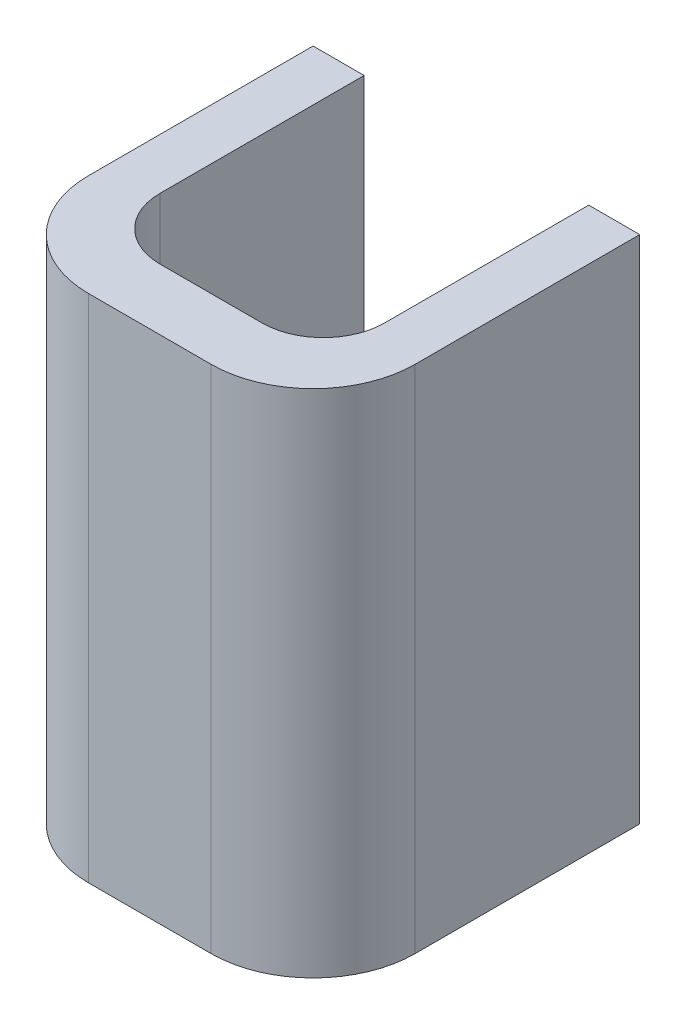
SolidWorks part; units mm, degrees
ref_plane "前视基准面" through (0, 0, 0) normal (0, 0, 1) x (1, 0, 0)
ref_plane "上视基准面" through (0, 0, 0) normal (0, 1, 0) x (1, 0, 0)
ref_plane "右视基准面" through (0, 0, 0) normal (1, 0, 0) x (0, 0, -1)
sketch "草图1" plane through (0, 0, 0) normal (0, 1, 0) x (1, 0, 0)
  line L0 (0, 0) -> (0, 7) construction
  line L1 (-8, -1.5) -> (8, -1.5)
  line L2 (-8, -1.5) -> (-8, 1.5)
  line L3 (-8, 1.5) -> (8, 1.5)
  line L4 (8, -1.5) -> (8, 1.5)
  line L5 (-8, -1.5) -> (8, 1.5) construction
  line L6 (-8, 1.5) -> (8, -1.5) construction
  line L7 (8, 1.5) -> (5.5, 1.5)
  line L8 (8, 1.5) -> (8, 14.5)
  line L9 (8, 14.5) -> (5.5, 14.5)
  line L10 (5.5, 1.5) -> (5.5, 14.5)
  line L11 (-8, 1.5) -> (-5.5, 1.5)
  line L12 (-5.5, 1.5) -> (-5.5, 14.5)
  line L13 (-8, 14.5) -> (-5.5, 14.5)
  line L14 (-8, 1.5) -> (-8, 14.5)
  point P0 (0, 0)
  point P14 (7.5, 12.8073)
  dimension "D1" = 11
  dimension "D2" = 5.5
  dimension "D3" = 2.5
  dimension "D4" = 3
  dimension "D5" = 13
extrude "凸台-拉伸1" add sketch "草图1" along normal blind 25 contours L10 L3 L8 L9 | L1 L4 L3 L2 | L14 L3 L12 L13
fillet "圆角1" radius 3 2 edges at (-5.5, 12.5, -1.5) (5.5, 12.5, -1.5)
fillet "圆角2" radius 5 2 edges at (8, 12.5, 1.5) (-8, 12.5, 1.5)
